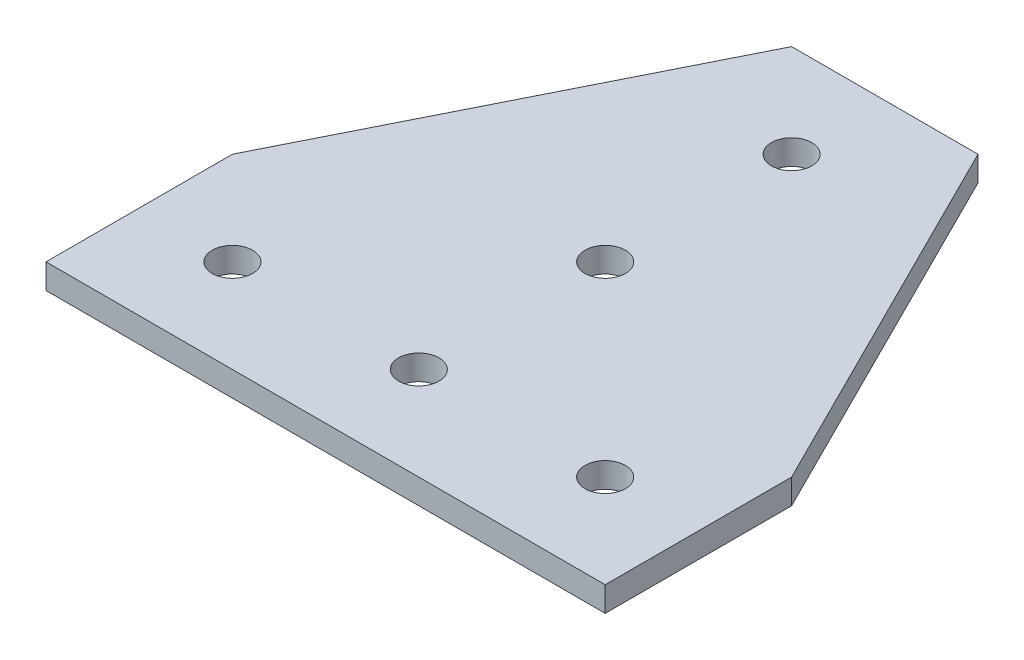
SolidWorks part; units mm, degrees
ref_plane "Front Plane" through (0, 0, 0) normal (0, 0, 1) x (1, 0, 0)
ref_plane "Top Plane" through (0, 0, 0) normal (0, 1, 0) x (1, 0, 0)
ref_plane "Right Plane" through (0, 0, 0) normal (1, 0, 0) x (0, 0, -1)
sketch "Sketch1" plane through (0, 0, 0) normal (0, 1, 0) x (1, 0, 0)
  line L0 (-45, 0) -> (45, 0)
  line L1 (-45, 0) -> (-45, 30)
  line L2 (-45, 30) -> (-15, 90)
  line L3 (-15, 90) -> (15, 90)
  line L4 (0, 90) -> (0, -27.1363) construction
  line L5 (45, 0) -> (45, 30)
  line L6 (45, 30) -> (15, 90)
  point P4 (0, 0)
  dimension "D1" = 90
  dimension "D2" = 30
  dimension "D3" = 30
  dimension "D4" = 90
extrude "Boss-Extrude1" add sketch "Sketch1" along normal blind 4
sketch "Sketch2" plane through (0, 4, 0) normal (0, 1, 0) x (1, 0, 0)
  line L0 (15, 90) -> (-15, 90) construction
  circle A0 centre (0, 75) radius 3.25
  circle A1 centre (0, 45) radius 3.25
  circle A2 centre (0, 15) radius 3.25
  circle A3 centre (30, 15) radius 3.25
  circle A4 centre (-30, 15) radius 3.25
  point P9 (0, 0)
  point P13 (0, 0)
  dimension "D5" = 6.5
  dimension "D8" = 30
  dimension "D1" = 15
  dimension "D3" = 2
  dimension "D6" = 30
  dimension "D7" = 30
  dimension "D2" = 3
  dimension "D4" = 2
extrude "Cut-Extrude1" cut sketch "Sketch2" against normal through all
